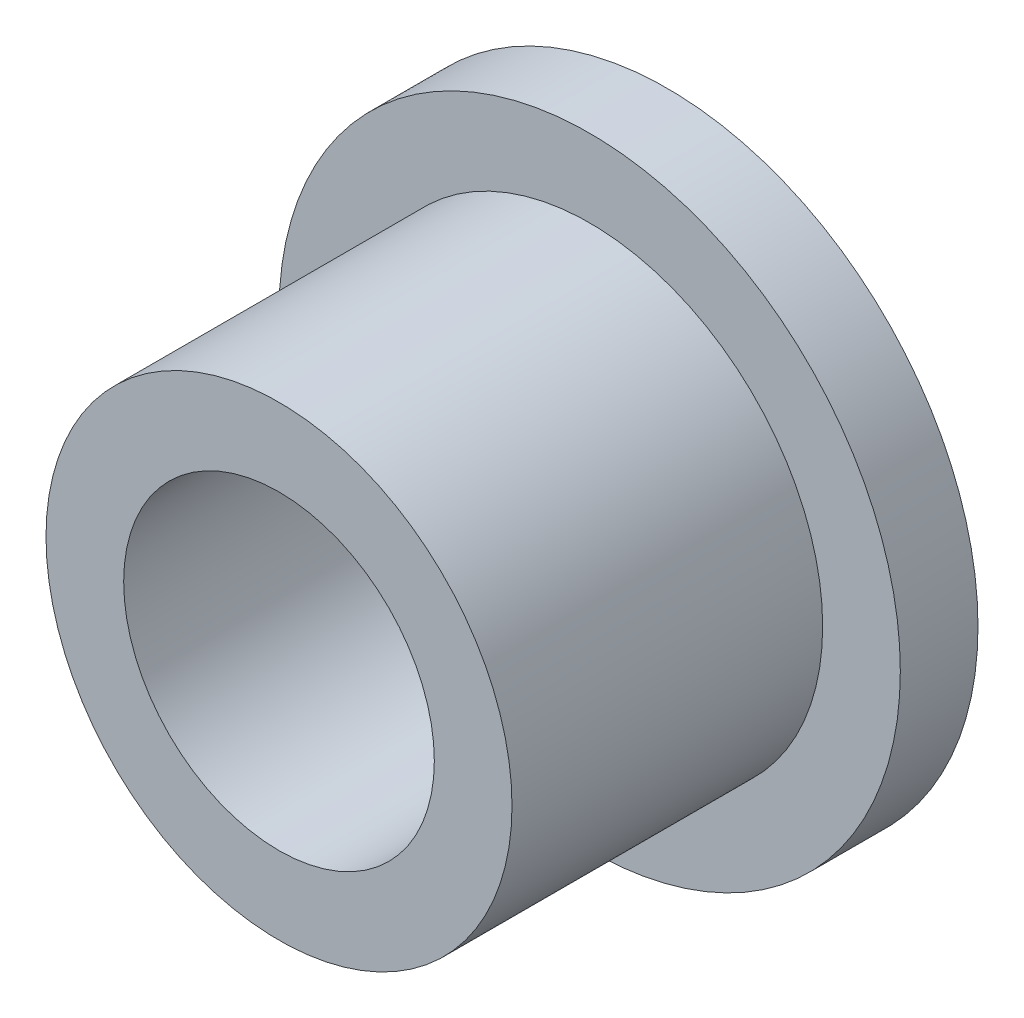
SolidWorks part; units mm, degrees
material "Aluminum Bronze"
ref_plane "Front Plane" through (0, 0, 0) normal (0, 0, 1) x (1, 0, 0)
ref_plane "Top Plane" through (0, 0, 0) normal (0, 1, 0) x (1, 0, 0)
ref_plane "Right Plane" through (0, 0, 0) normal (1, 0, 0) x (0, 0, -1)
sketch "Sketch1" plane through (0, 0, 0) normal (0, 0, 1) x (1, 0, 0)
  circle A0 centre (0, 0) radius 3.175
  circle A1 centre (0, 0) radius 6.35
  dimension "D1" = 6.35
  dimension "D2" = 12.7
extrude "Boss-Extrude1" add sketch "Sketch1" along normal blind 1.5875
sketch "Sketch2" plane through (0, 0, 1.5875) normal (0, 0, 1) x (1, 0, 0)
  circle A0 centre (0, 0) radius 3.175
  circle A1 centre (0, 0) radius 4.7625
  circle A2 centre (0, 0) radius 3.175 construction
  dimension "D1" = 9.525
extrude "Boss-Extrude2" add sketch "Sketch2" along normal blind 6.35
